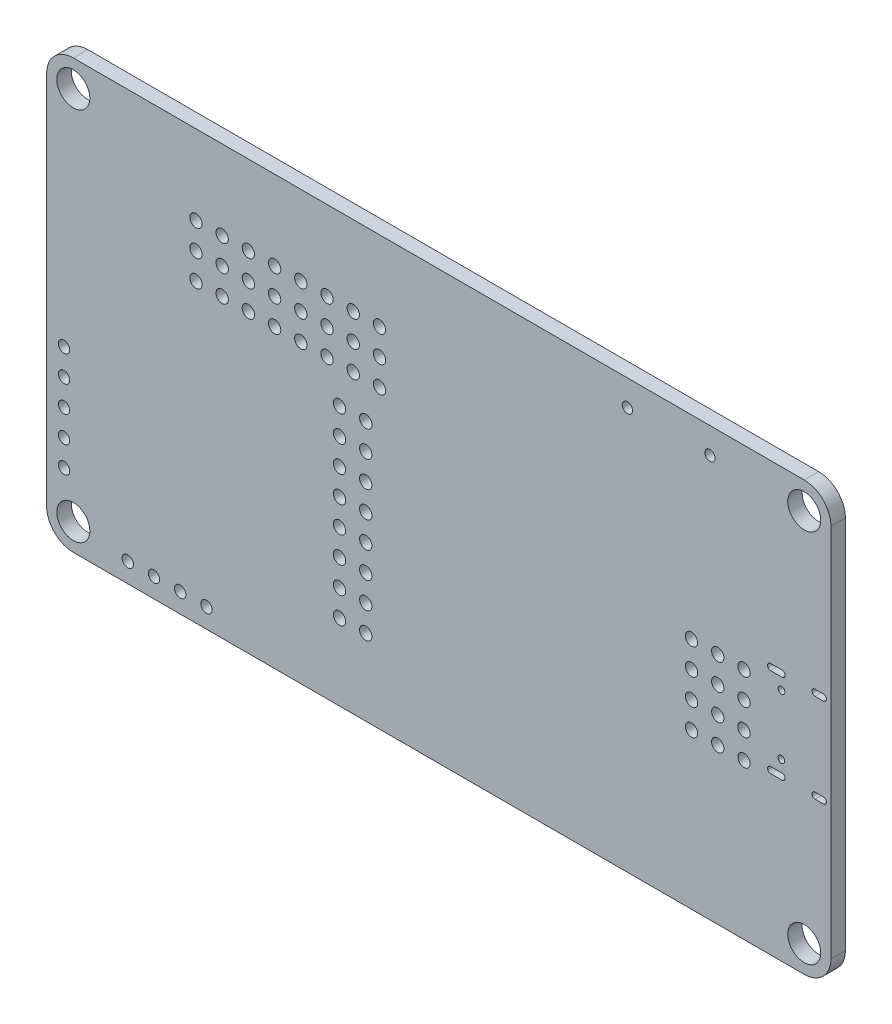
SolidWorks part; units mm, degrees
ref_plane "前视基准面" through (0, 0, 0) normal (0, 0, 1) x (1, 0, 0)
ref_plane "上视基准面" through (0, 0, 0) normal (0, 1, 0) x (1, 0, 0)
ref_plane "右视基准面" through (0, 0, 0) normal (1, 0, 0) x (0, 0, -1)
ref_plane "基准面1" through (0, 0, 1.399) normal (0, 0, 1) x (1, 0, 0)
sketch "草图1" plane through (0, 0, 1.399) normal (0, 0, 1) x (1, 0, 0)
  line L0 (107.6124, 157.8158) -> (108.7124, 157.8158)
  line L1 (108.7124, 157.2158) -> (107.6124, 157.2158)
  line L2 (111.9125, 157.8158) -> (112.7125, 157.8158)
  line L3 (112.7125, 157.2158) -> (111.9125, 157.2158)
  line L4 (107.6124, 149.1757) -> (108.7124, 149.1757)
  line L5 (108.7124, 148.5757) -> (107.6124, 148.5757)
  line L6 (111.9125, 149.1757) -> (112.7125, 149.1757)
  line L7 (112.7125, 148.5757) -> (111.9125, 148.5757)
  line L8 (40.0651, 133.363) -> (110.8651, 133.363)
  line L9 (113.4524, 135.9503) -> (113.4524, 172.2503)
  line L10 (110.8651, 174.8376) -> (40.0651, 174.8376)
  line L11 (37.4778, 172.2503) -> (37.4778, 135.9503)
  circle A0 centre (40.0651, 172.2503) radius 1.6
  circle A1 centre (51.9431, 167.1323) radius 0.5994
  circle A2 centre (54.4831, 167.1323) radius 0.5994
  circle A3 centre (57.0231, 167.1323) radius 0.5994
  circle A4 centre (51.9431, 164.5923) radius 0.5994
  circle A5 centre (54.4831, 164.5923) radius 0.5994
  circle A6 centre (57.0231, 164.5923) radius 0.5994
  circle A7 centre (59.5631, 167.1323) radius 0.5994
  circle A8 centre (62.1031, 167.1323) radius 0.5994
  circle A9 centre (64.6431, 167.1323) radius 0.5994
  circle A10 centre (59.5631, 164.5923) radius 0.5994
  circle A11 centre (62.1031, 164.5923) radius 0.5994
  circle A12 centre (64.6431, 164.5923) radius 0.5994
  circle A13 centre (67.1831, 167.1323) radius 0.5994
  circle A14 centre (69.7231, 167.1323) radius 0.5994
  circle A15 centre (67.1831, 164.5923) radius 0.5994
  circle A16 centre (69.7231, 164.5923) radius 0.5994
  circle A17 centre (51.9431, 162.0523) radius 0.5994
  circle A18 centre (54.4831, 162.0523) radius 0.5994
  circle A19 centre (57.0231, 162.0523) radius 0.5994
  circle A20 centre (59.5631, 162.0523) radius 0.5994
  circle A21 centre (62.1031, 162.0523) radius 0.5994
  circle A22 centre (64.6431, 162.0523) radius 0.5994
  circle A23 centre (67.1831, 162.0523) radius 0.5994
  circle A24 centre (69.7231, 162.0523) radius 0.5994
  circle A25 centre (65.8514, 158.5242) radius 0.6
  circle A26 centre (65.8514, 155.9842) radius 0.6
  circle A27 centre (68.3914, 158.5242) radius 0.6
  circle A28 centre (68.3914, 155.9842) radius 0.6
  circle A29 centre (93.7342, 172.3343) radius 0.5
  circle A30 centre (101.7342, 172.3343) radius 0.5
  circle A31 centre (110.8651, 172.2503) radius 1.6
  circle A32 centre (99.9492, 156.0198) radius 0.5994
  circle A33 centre (102.4892, 156.0198) radius 0.5994
  arc A34 (108.7124, 157.8158) -> (108.7124, 157.2158) centre (108.7124, 157.5158) cw
  arc A35 (107.6124, 157.2158) -> (107.6124, 157.8158) centre (107.6124, 157.5158) cw
  arc A36 (112.7125, 157.8158) -> (112.7125, 157.2158) centre (112.7125, 157.5158) cw
  arc A37 (111.9125, 157.2158) -> (111.9125, 157.8158) centre (111.9125, 157.5158) cw
  circle A38 centre (105.0292, 156.0198) radius 0.5994
  circle A39 centre (108.6625, 156.0957) radius 0.325
  circle A40 centre (39.1683, 150.1636) radius 0.55
  circle A41 centre (39.1683, 147.6236) radius 0.55
  circle A42 centre (39.1683, 145.0836) radius 0.55
  circle A43 centre (65.8514, 153.4442) radius 0.6
  circle A44 centre (65.8514, 150.9041) radius 0.6
  circle A45 centre (68.3914, 153.4442) radius 0.6
  circle A46 centre (68.3914, 150.9041) radius 0.6
  circle A47 centre (65.8514, 148.3641) radius 0.6
  circle A48 centre (65.8514, 145.8241) radius 0.6
  circle A49 centre (68.3914, 148.3641) radius 0.6
  circle A50 centre (68.3914, 145.8241) radius 0.6
  circle A51 centre (39.1683, 142.5436) radius 0.55
  circle A52 centre (39.1683, 140.0036) radius 0.55
  circle A53 centre (40.0651, 135.9503) radius 1.6
  circle A54 centre (45.3391, 135.2553) radius 0.55
  circle A55 centre (47.8791, 135.2553) radius 0.55
  circle A56 centre (50.4191, 135.2553) radius 0.55
  circle A57 centre (52.9591, 135.2553) radius 0.55
  circle A58 centre (65.8514, 143.2841) radius 0.6
  circle A59 centre (65.8514, 140.7441) radius 0.6
  circle A60 centre (68.3914, 143.2841) radius 0.6
  circle A61 centre (68.3914, 140.7441) radius 0.6
  circle A62 centre (99.9492, 153.4798) radius 0.5994
  circle A63 centre (102.4892, 153.4798) radius 0.5994
  circle A64 centre (99.9492, 150.9398) radius 0.5994
  circle A65 centre (102.4892, 150.9398) radius 0.5994
  circle A66 centre (105.0292, 153.4798) radius 0.5994
  circle A67 centre (105.0292, 150.9398) radius 0.5994
  circle A68 centre (108.6524, 150.2958) radius 0.325
  circle A69 centre (99.9492, 148.3998) radius 0.5994
  circle A70 centre (102.4892, 148.3998) radius 0.5994
  circle A71 centre (105.0292, 148.3998) radius 0.5994
  arc A72 (108.7124, 149.1757) -> (108.7124, 148.5757) centre (108.7124, 148.8757) cw
  arc A73 (107.6124, 148.5757) -> (107.6124, 149.1757) centre (107.6124, 148.8757) cw
  arc A74 (112.7125, 149.1757) -> (112.7125, 148.5757) centre (112.7125, 148.8757) cw
  arc A75 (111.9125, 148.5757) -> (111.9125, 149.1757) centre (111.9125, 148.8757) cw
  circle A76 centre (110.8651, 135.9503) radius 1.6
  arc A77 (110.8651, 133.363) -> (113.4524, 135.9503) centre (110.8651, 135.9503) ccw
  arc A78 (113.4524, 172.2503) -> (110.8651, 174.8376) centre (110.8651, 172.2503) ccw
  arc A79 (40.0651, 174.8376) -> (37.4778, 172.2503) centre (40.0651, 172.2503) ccw
  arc A80 (37.4778, 135.9503) -> (40.0651, 133.363) centre (40.0651, 135.9503) ccw
extrude "凸台-拉伸1" add sketch "草图1" against normal blind 1.399
